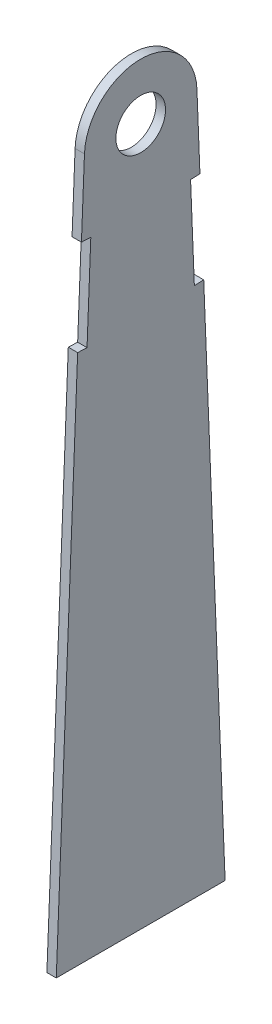
SolidWorks part; units mm, degrees
material "AISI 4130 Steel, annealed at 865C"
ref_plane "X-Y Datum" through (0, 0, 0) normal (0, 0, 1) x (1, 0, 0)
ref_plane "X-Z Datum" through (0, 0, 0) normal (0, 1, 0) x (1, 0, 0)
ref_plane "Y-Z Datum" through (0, 0, 0) normal (1, 0, 0) x (0, 0, -1)
sketch "Sketch1" plane through (0, 0, 0) normal (1, 0, 0) x (0, 0, -1)
  line L0 (0, -118.0251) -> (-14.2875, -118.0251)
  line L1 (-14.2875, -118.0251) -> (-9.5173, 0.3834)
  line L2 (0, -118.0251) -> (14.2875, -118.0251)
  line L3 (14.2875, -118.0251) -> (9.5173, 0.3834)
  line L4 (0, -118.0251) -> (0, 0) construction
  line L5 (-10.6675, -28.1684) -> (-9.0813, -28.2323)
  line L10 (-10.6675, -28.1684) -> (-10.0285, -12.3063)
  line L11 (-9.0813, -28.2323) -> (-8.4423, -12.3702)
  line L12 (-10.0285, -12.3063) -> (-8.4423, -12.3702)
  line L13 (10.6675, -28.1684) -> (10.0285, -12.3063)
  line L14 (10.6675, -28.1684) -> (9.0813, -28.2323)
  line L15 (10.0285, -12.3063) -> (8.4423, -12.3702)
  line L16 (9.0813, -28.2323) -> (8.4423, -12.3702)
  arc A0 (9.5173, 0.3834) -> (-9.5173, 0.3834) centre (0, 0) ccw
  dimension "D1" = 9.525
  dimension "D2" = 14.2875
  dimension "D3" = 14.2875
  dimension "D4" = 118.0251
  dimension "D5" = 1.5875
  dimension "D6" = 15.875
  dimension "D7" = 12.7
  dimension "D8" = 12.7
extrude "Boss-Extrude1" add sketch "Sketch1" along normal blind 1.5875
hole_wizard "M8 Clearance Hole1" positions "Sketch2" profile "Sketch3" hole size "M8" standard "ANSI Metric" end condition through all
sketch "Sketch2" plane through (1.5875, 0, 0) normal (1, 0, 0) x (0, 0, -1)
  point P0 (0, 0)
sketch "Sketch3" plane through (1.5875, 0, 0) normal (0, 1, 0) x (0, 0, -1)
  line L0 (0, 0) -> (0, 1.5875)
  line L1 (0, 1.5875) -> (4.2, 1.5875)
  line L2 (4.2, 1.5875) -> (4.2, 0)
  line L5 (4.2, 0) -> (0, 0)
  line L11 (0, -6.35) -> (0, 107.95) construction
  dimension "Thru Hole Dia." = 8.4
  dimension "Thru Hole Depth" = 1.5875
sketch "Sketch4" plane through (1.5875, 0, 0) normal (1, 0, 0) x (0, 0, -1)
  line L2 (10.0285, -12.3063) -> (9.5173, 0.3834) construction
  line L3 (-10.0285, -12.3063) -> (-9.5173, 0.3834) construction
  line L5 (9.6977, -4.0943) -> (9.5173, 0.3834)
  line L6 (-9.6977, -4.0943) -> (-9.5173, 0.3834)
  arc A3 (9.5173, 0.3834) -> (-9.5173, 0.3834) centre (0, 0) ccw construction
  arc A4 (9.5173, 0.3834) -> (-9.5173, 0.3834) centre (0, 0) ccw
  ellipse E0 centre (0, -4.7625) end of major axis (0, 7.9375) minor radius 9.7111 (9.6977, -4.0943) -> (-9.6977, -4.0943) ccw
  point P7 (0, 7.9375)
  dimension "D1" = 7.9375
  dimension "D2" = 4.7625
extrude "Cut-Extrude1" [suppressed] cut sketch "Sketch4" against normal through all
equation "\"D8@Sketch1\"=\"D7@Sketch1\""
equation "\"D3@Sketch1\"=\"D2@Sketch1\""
